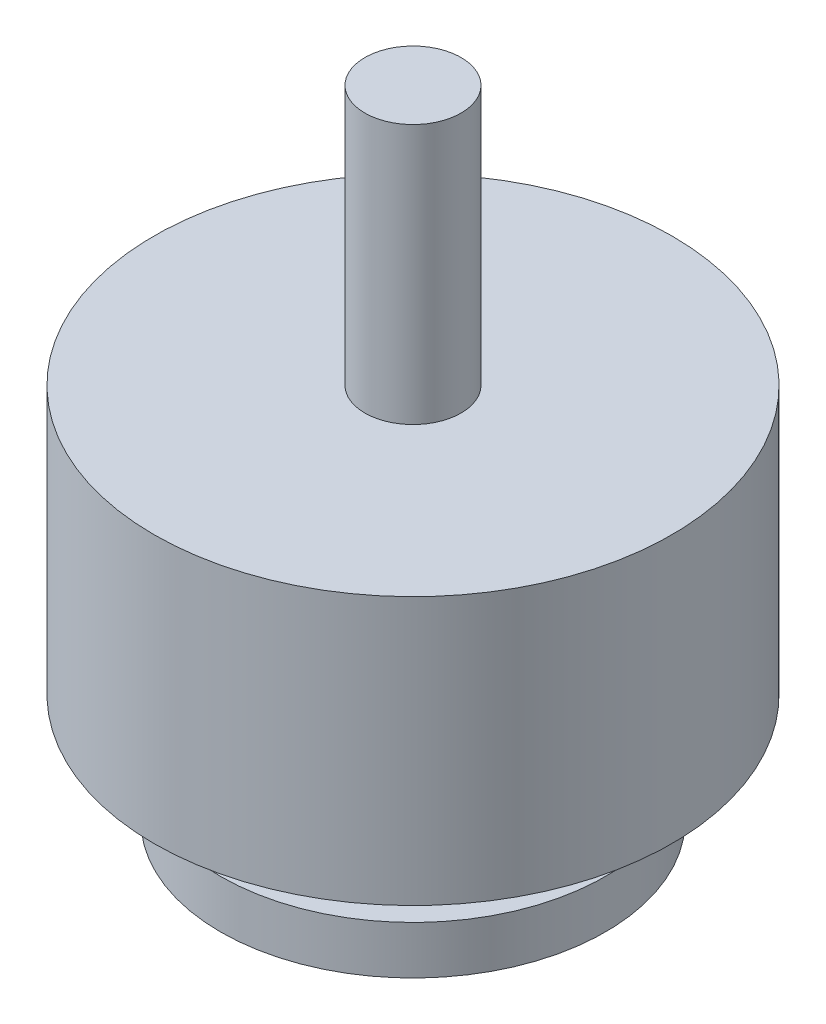
SolidWorks part; units mm, degrees
ref_plane "Front Plane" through (0, 0, 0) normal (0, 0, 1) x (1, 0, 0)
ref_plane "Top Plane" through (0, 0, 0) normal (0, 1, 0) x (1, 0, 0)
ref_plane "Right Plane" through (0, 0, 0) normal (1, 0, 0) x (0, 0, -1)
sketch "Sketch1" plane through (0, 0, 0) normal (0, 1, 0) x (1, 0, 0)
  circle A0 centre (0, 0) radius 13.45
  dimension "D1" = 26.9
extrude "Boss-Extrude1" add sketch "Sketch1" along normal blind 13.9
ref_plane "Plane1" through (0, -5.7, 0) normal (0, 1, 0) x (1, 0, 0)
sketch "Sketch2" plane through (0, -5.7, 0) normal (0, -1, 0) x (1, 0, 0)
  circle A0 centre (0, 0) radius 10
  circle A1 centre (0, 0) radius 8 construction
  circle A2 centre (0, 8) radius 1.5
  circle A3 centre (8, 0) radius 1.5
  circle A4 centre (0, -8) radius 1.5
  circle A5 centre (-8, 0) radius 1.5
  dimension "D1" = 16
  dimension "D2" = 3
  dimension "D3" = 20
extrude "Boss-Extrude3" add sketch "Sketch2" against normal blind 2.5 separate body
sketch "Sketch3" plane through (0, -3.2, 0) normal (0, 1, 0) x (1, 0, 0)
  circle A0 centre (0, 0) radius 5
  dimension "D1" = 10
extrude "Boss-Extrude4" add sketch "Sketch3" along normal up to body separate body
sketch "Sketch4" plane through (0, 13.9, 0) normal (0, 1, 0) x (1, 0, 0)
  circle A0 centre (0, 0) radius 2.5
  dimension "D1" = 5
extrude "Boss-Extrude5" add sketch "Sketch4" along normal blind 13.5
